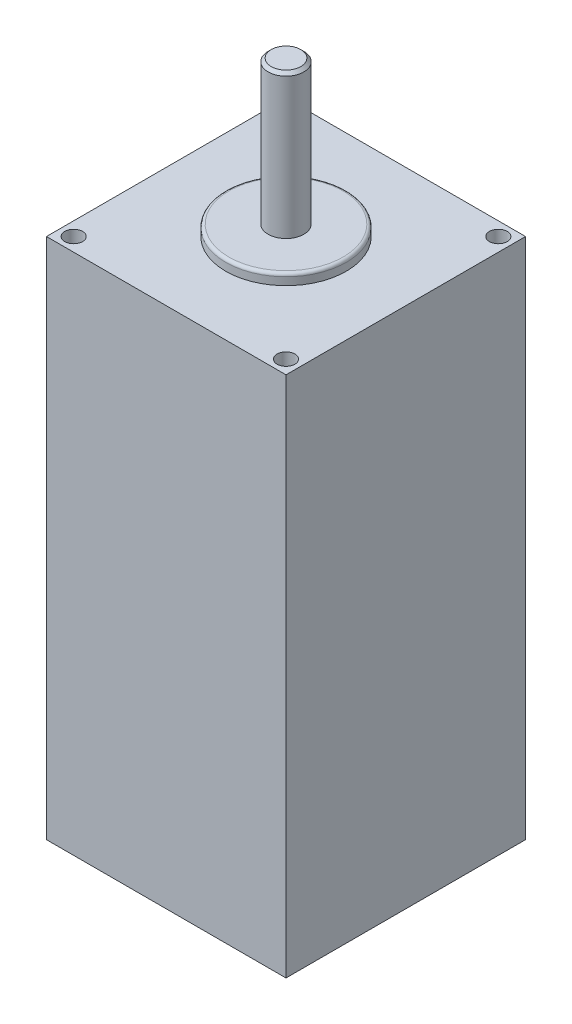
SolidWorks part; units mm, degrees
ref_plane "Front Plane" through (0, 0, 0) normal (0, 0, 1) x (1, 0, 0)
ref_plane "Top Plane" through (0, 0, 0) normal (0, 1, 0) x (1, 0, 0)
ref_plane "Right Plane" through (0, 0, 0) normal (1, 0, 0) x (0, 0, -1)
sketch "Sketch1" plane through (0, 0, 0) normal (0, 0, 1) x (1, 0, 0)
  line L1 (0, 0) -> (39.37, 0)
  line L2 (0, 0) -> (0, 85.852)
  line L3 (0, 85.852) -> (39.37, 85.852)
  line L4 (39.37, 0) -> (39.37, 85.852)
  dimension "D1" = 85.852
  dimension "D2" = 39.37
extrude "Extrude1" add sketch "Sketch1" against normal blind 39.37
sketch "Sketch2" plane through (0, 85.852, 0) normal (0, 1, 0) x (1, 0, 0)
  line L0 (0, 39.37) -> (39.37, 0) construction
  line L1 (0, 0) -> (39.37, 39.37) construction
  circle A0 centre (19.685, 19.685) radius 2.9337
  dimension "D1" = 5.8674
extrude "Extrude2" add sketch "Sketch2" along normal blind 25.4
chamfer "Chamfer1" distance 0.508 angle 45 1 edges at (19.685, 111.252, -16.7513)
sketch "Sketch4" plane through (0, 85.852, 0) normal (0, 1, 0) x (1, 0, 0)
  line L0 (0, 39.37) -> (39.37, 0) construction
  line L1 (0, 0) -> (39.37, 39.37) construction
  line L2 (39.37, 39.37) -> (0, 39.37) construction
  line L3 (39.37, 39.37) -> (39.37, 0) construction
  circle A0 centre (19.685, 19.685) radius 9.906
  dimension "D1" = 19.812
extrude "Extrude3" add sketch "Sketch4" along normal blind 1.778
fillet "Fillet3" radius 0.508 1 edges at (19.685, 87.63, -9.779)
sketch "Sketch5" plane through (0, 85.852, 0) normal (0, 1, 0) x (1, 0, 0)
  line L0 (0, 0) -> (39.37, 39.37) construction
  line L1 (0, 39.37) -> (39.37, 0) construction
  line L2 (39.37, 0) -> (0, 0) construction
  circle A0 centre (19.685, 19.685) radius 24.6761 construction
  circle A1 centre (2.2364, 37.1336) radius 1.4605
  circle A2 centre (37.1336, 37.1336) radius 1.4605
  circle A3 centre (37.1336, 2.2364) radius 1.4605
  circle A4 centre (2.2364, 2.2364) radius 1.4605
  dimension "D1" = 49.3522
  dimension "D2" = 2.921
  dimension "D3" = 2.921
  dimension "D4" = 2.921
  dimension "D5" = 2.921
extrude "Extrude4" cut sketch "Sketch5" against normal blind 12.7
